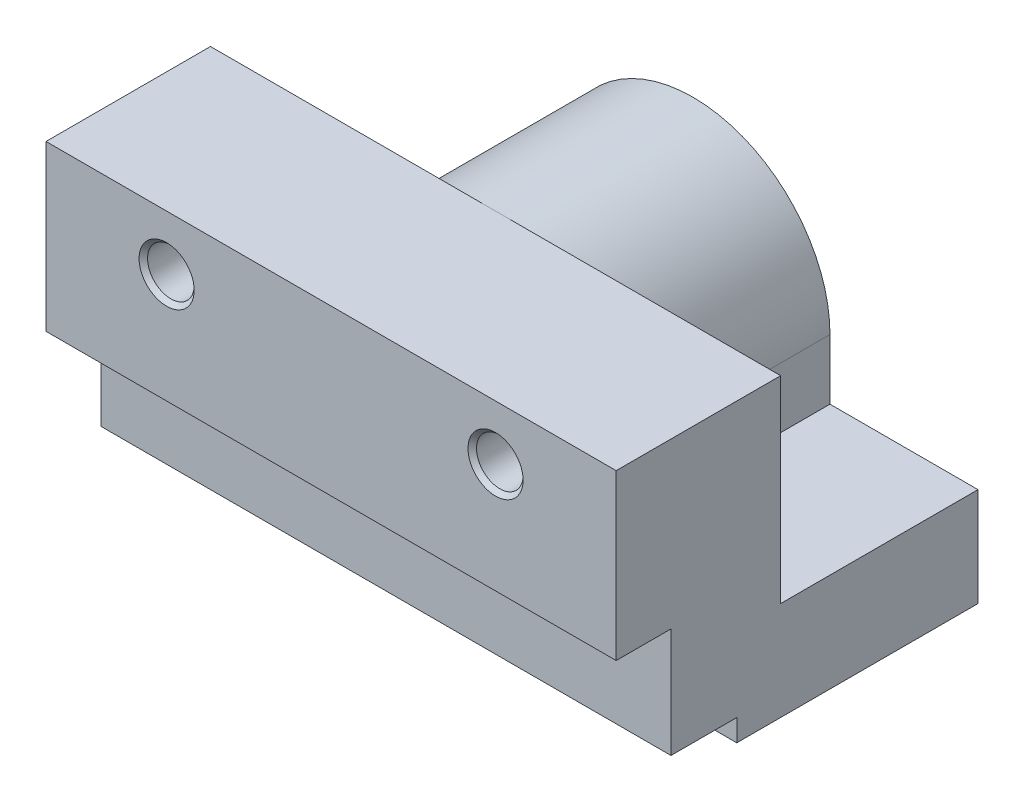
SolidWorks part; units mm, degrees
ref_plane "Alzado" through (0, 0, 0) normal (0, 0, 1) x (1, 0, 0)
ref_plane "Planta" through (0, 0, 0) normal (0, 1, 0) x (1, 0, 0)
ref_plane "Vista lateral" through (0, 0, 0) normal (1, 0, 0) x (0, 0, -1)
sketch "Croquis2" plane through (0, 0, 0) normal (0, 0, 1) x (1, 0, 0)
  line L1 (-52, 0) -> (52, 0)
  line L2 (-52, 0) -> (-52, 54)
  line L3 (-52, 54) -> (52, 54)
  line L4 (52, 0) -> (52, 54)
  point P4 (0, 0)
  dimension "D1" = 104
  dimension "D2" = 54
  dimension "D3" = 0
  dimension "D4" = 0
extrude "Saliente-Extruir1" add sketch "Croquis2" along normal blind 66
sketch "Croquis3" plane through (0, 0, 0) normal (0, 0, 1) x (1, 0, 0)
  line L0 (52, 0) -> (50052, 0) construction
  line L1 (-1156, 54) -> (-52, 54) construction
  line L2 (52, 54) -> (52, 50054) construction
  line L3 (-52, -996) -> (-52, 18) construction
  line L4 (0, 0) -> (0, 50000) construction
  line L5 (62.5868, 18) -> (25, 18) construction
  line L6 (25, 70.3117) -> (25, -49929.6883) construction
  line L7 (-25, 54) -> (-25, 29) construction
  line L8 (25, 29) -> (25, 18)
  line L9 (-942.4683, 29) -> (-25, 29) construction
  line L11 (-52, 18) -> (-49937.4132, 18) construction
  line L12 (25, 18) -> (52, 18)
  line L13 (52, 18) -> (52, 54)
  line L14 (52, 54) -> (0, 54)
  line L15 (0, 54) -> (50052, 54) construction
  line L16 (-25, 18) -> (-25, -49929.9922) construction
  line L17 (-52, 54) -> (-52, 50054) construction
  line L19 (25, 29) -> (49057.5317, 29) construction
  arc A0 (0, 54) -> (25, 29) centre (0, 29) cw
  point P23 (0, 18)
  dimension "D1" = 18
  dimension "D2" = 50
  dimension "D3" = 25
  dimension "D4" = 11
extrude "Cortar-Extruir1" cut sketch "Croquis3" along normal blind 36
ref_plane "Plano1" through (0, 0, 0) normal (1, 0, 0) x (0, 0, -1)
mirror "Simetría1" about plane through (0, 0, 0) normal (1, 0, 0) of "Cortar-Extruir1"
sketch "Croquis4" plane through (0, 0, 0) normal (0, 0, 1) x (1, 0, 0)
  line L0 (0, 0) -> (0, 50000) construction
  line L1 (25, 18) -> (-49975, 18) construction
  line L2 (-52, 0) -> (52, 0) construction
  circle A0 centre (0, 28) radius 8
  dimension "D1" = 16
  dimension "D2" = 28
hole_wizard "Taladros de espiga de Ø16.0mm1" positions "Croquis5" profile "Croquis6" hole size "Ø16.0" standard "ISO"
sketch "Croquis5" plane through (0, 0, 0) normal (0, 0, -1) x (-1, 0, 0)
  point P0 (0, 28)
sketch "Croquis6" plane through (0, 28, 0) normal (1, 0, 0) x (0, 1, 0)
  line L0 (0, 0) -> (0, 40.8069)
  line L1 (0, 40.8069) -> (8, 36)
  line L2 (8, 36) -> (8, 0.025)
  line L3 (8, 0.025) -> (8.025, 0)
  line L5 (8.025, 0) -> (0, 0)
  line L6 (-8, 0.025) -> (-8.025, 0) construction
  line L10 (0, 40.8069) -> (-8, 36) construction
  line L11 (0, -6.35) -> (0, 107.95) construction
  dimension "Diámetro de taladro" = 16
  dimension "Profundidad de taladro" = 36
  dimension "Diámetro de avellanado cercano" = 16.05
  dimension "Ángulo de avellanado cercano" = 90
  dimension "Ángulo de perforador" = 118
sketch "Croquis7" plane through (0, 0, 0) normal (0, 1, 0) x (1, 0, 0)
  line L0 (0, 0) -> (0, -50000) construction
  line L1 (200025, 0) -> (-249975, 0) construction
  line L3 (0, -44) -> (-50000, -44) construction
  line L4 (-14, -40.8167) -> (-14, 49959.1833) construction
  line L5 (14, -40.8167) -> (14, 49959.1833) construction
  line L6 (-14, -44) -> (14, -44)
  line L7 (-14, -44) -> (-14, 0)
  line L8 (-14, 0) -> (14, 0)
  line L9 (14, -44) -> (14, 0)
  dimension "D1" = 44
  dimension "D2" = 28
  dimension "D3" = 14
extrude "Saliente-Extruir2" add sketch "Croquis7" against normal blind 4
sketch "Croquis8" plane through (0, 0, 0) normal (1, 0, 0) x (0, 0, -1)
  line L0 (-66, 0) -> (-66, 54) construction
  line L1 (-44, 0) -> (-56.4949, 0)
  line L2 (-44, 0) -> (-44, 4)
  line L3 (-44, 4) -> (-56, 4)
  line L5 (-56.4949, 0) -> (-66, 0)
  line L6 (-56, 4) -> (-56, 24)
  line L7 (-56, 24) -> (-66, 24)
  line L8 (-66, 0) -> (-66, 24)
  line L9 (-66, 0) -> (-66, -50000) construction
  line L10 (-44, -4) -> (-44, -50004) construction
  dimension "D1" = 4
  dimension "D2" = 24
  dimension "D3" = 10
extrude "Cortar-Extruir3" cut sketch "Croquis8" against normal through all and the other way through all
sketch "Croquis9" plane through (0, 0, 0) normal (1, 0, 0) x (0, 0, -1)
  line L0 (0, 54) -> (0, 50054) construction
  line L2 (-36, 18) -> (-36, 50018) construction
  line L3 (0, 29) -> (50000, 29) construction
  line L4 (-18, 29) -> (-18, 50029) construction
  line L5 (-36, 29) -> (0, 29) construction
  circle A0 centre (-18, 29) radius 2
  point P13 (-18, 29)
  point P15 (0, 0)
  dimension "D1" = 4
extrude "Cortar-Extruir4" cut sketch "Croquis9" against normal through all and the other way through all
ref_plane "Plano2" through (0, 0, 66) normal (0, 0, 1) x (1, 0, 0)
sketch "Croquis11" plane through (0, 0, 66) normal (0, 0, 1) x (1, 0, 0)
  line L0 (30, 63.4776) -> (30, -49936.5224) construction
  line L1 (52, 54) -> (52, 50054) construction
  line L2 (52, 54) -> (50052, 54) construction
  line L3 (69.0878, 44) -> (-49930.9122, 44) construction
  dimension "D1" = 22
  dimension "D2" = 10
hole_wizard "Taladro roscado M101" positions "Croquis12" profile "Croquis13" tap size "M10" standard "ISO"
sketch "Croquis12" plane through (0, 0, 66) normal (0, 0, 1) x (1, 0, 0)
  line L0 (30, 200063.4776) -> (30, -249936.5224) construction
  line L1 (200069.0878, 44) -> (-249930.9122, 44) construction
  point P0 (30, 44)
sketch "Croquis13" plane through (30, 44, 66) normal (1, 0, 0) x (0, -1, 0)
  line L0 (0, 0) -> (0, 11.5537)
  line L1 (0, 11.5537) -> (4.25, 9)
  line L2 (4.25, 9) -> (4.25, 0.775)
  line L3 (4.25, 0.775) -> (5.025, 0)
  line L5 (5.025, 0) -> (0, 0)
  line L6 (-4.25, 0.775) -> (-5.025, 0) construction
  line L10 (0, 11.5537) -> (-4.25, 9) construction
  line L11 (0, -6.35) -> (0, 107.95) construction
  dimension "Diámetro de perforador para roscar" = 8.5
  dimension "Profundidad de perforador para roscar" = 9
  dimension "Diámetro de avellanado cercano" = 10.05
  dimension "Ángulo de avellanado cercano" = 90
  dimension "Ángulo de perforador" = 118
cosmetic thread "Rosca de taladro1" parameters "D1"=20, "D2"=10
ref_plane "Plano3" through (0, 0, 0) normal (-1, 0, 0) x (0, 0, 1)
mirror "Simetría2" about plane through (0, 0, 0) normal (-1, 0, 0) of "Taladro roscado M101"
cosmetic thread "Rosca de taladro2" parameters "D1"=20, "D2"=10
ref_plane "Plano4" through (0, -4, 0) normal (0, -1, 0) x (-1, 0, 0)
sketch "Croquis15" plane through (0, -4, 0) normal (0, -1, 0) x (-1, 0, 0)
  line L0 (14, 0) -> (50014, 0) construction
  line L2 (14, -44) -> (50014, -44) construction
  line L4 (2.5577, -14) -> (50002.5577, -14) construction
  line L5 (7.1657, -36) -> (50007.1657, -36) construction
  dimension "D1" = 36
  dimension "D2" = 22
hole_wizard "Taladro roscado M102" positions "Croquis18" profile "Croquis19" tap size "M10" standard "ISO"
sketch "Croquis18" plane through (0, -4, 0) normal (0, -1, 0) x (-1, 0, 0)
  line L0 (-199992.8343, -36) -> (250007.1657, -36) construction
  line L1 (0, -29.7) -> (0, 29.7) construction
  line L2 (-199997.4423, -14) -> (250002.5577, -14) construction
  point P0 (0, -36)
  point P6 (0, -14)
sketch "Croquis19" plane through (0, -4, 36) normal (1, 0, 0) x (0, 0, -1)
  line L0 (0, 0) -> (0, 30.0537)
  line L1 (0, 30.0537) -> (4.25, 27.5)
  line L2 (4.25, 27.5) -> (4.25, 0.775)
  line L3 (4.25, 0.775) -> (5.025, 0)
  line L5 (5.025, 0) -> (0, 0)
  line L6 (-4.25, 0.775) -> (-5.025, 0) construction
  line L10 (0, 30.0537) -> (-4.25, 27.5) construction
  line L11 (0, -6.35) -> (0, 107.95) construction
  dimension "Diámetro de perforador para roscar" = 8.5
  dimension "Profundidad de perforador para roscar" = 27.5
  dimension "Diámetro de avellanado cercano" = 10.05
  dimension "Ángulo de avellanado cercano" = 90
  dimension "Ángulo de perforador" = 118
cosmetic thread "Rosca de taladro3" parameters "D1"=20, "D2"=10
cosmetic thread "Rosca de taladro4" parameters "D1"=20, "D2"=10
